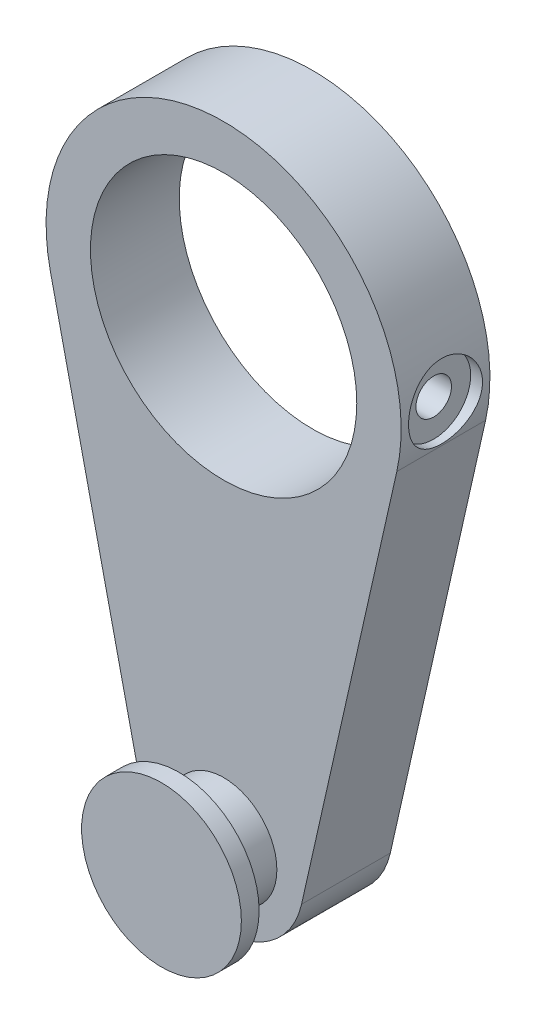
SolidWorks part; units mm, degrees
ref_plane "Front Plane" through (0, 0, 0) normal (0, 0, 1) x (1, 0, 0)
ref_plane "Top Plane" through (0, 0, 0) normal (0, 1, 0) x (1, 0, 0)
ref_plane "Right Plane" through (0, 0, 0) normal (1, 0, 0) x (0, 0, -1)
other "Configuration Table"
sketch "Sketch1" plane through (0, 0, 0) normal (0, 0, 1) x (1, 0, 0)
  line L0 (-4.9555, -1.1176) -> (-2.23, -13.2029)
  line L1 (2.23, -13.2029) -> (4.9555, -1.1176)
  circle A0 centre (0, 0) radius 5.08
  circle A1 centre (0, -12.7) radius 2.286
  circle A2 centre (0, 0) radius 3.81
  dimension "D1" = 10.16
  dimension "D2" = 7.62
  dimension "D3" = 4.572
  dimension "D4" = 12.7
extrude "Boss-Extrude1" add sketch "Sketch1" along normal blind 2.54 contours A0 A2 | A1 L1 A0 L0 | A1
sketch "Sketch2" plane through (0, 0, 2.54) normal (0, 0, 1) x (1, 0, 0)
  circle A0 centre (0, -12.7) radius 1.524
  dimension "D1" = 3.048
extrude "Boss-Extrude2" add sketch "Sketch2" along normal blind 1.27
sketch "Sketch3" plane through (0, 0, 3.81) normal (0, 0, 1) x (1, 0, 0)
  circle A0 centre (0, -12.7) radius 2.286
  dimension "D1" = 4.572
extrude "Boss-Extrude3" add sketch "Sketch3" along normal blind 0.508
scale "Scale1" scale about centroid uniform scaling yes scale factor 1.5
sketch "Sketch4" plane through (0, 0, 0) normal (1, 0, 0) x (0, 0, -1)
  line L0 (-1.1939, 10.6656) -> (-1.1939, 3.0456) construction
  line L1 (0.7111, 10.6656) -> (-3.0989, 10.6656) construction
  line L2 (-3.0989, 3.0456) -> (0.7111, 3.0456) construction
  circle A0 centre (-1.1939, 3.0456) radius 1.5875
  dimension "D1" = 3.175
extrude "Cut-Extrude1" cut sketch "Sketch4" along normal blind 10 from offset 7.112
sketch "Sketch5" plane through (0, 0, 0) normal (1, 0, 0) x (0, 0, -1)
  circle A0 centre (-1.1939, 3.0456) radius 0.762
  dimension "D1" = 1.524
extrude "Cut-Extrude2" cut sketch "Sketch5" along normal through all
